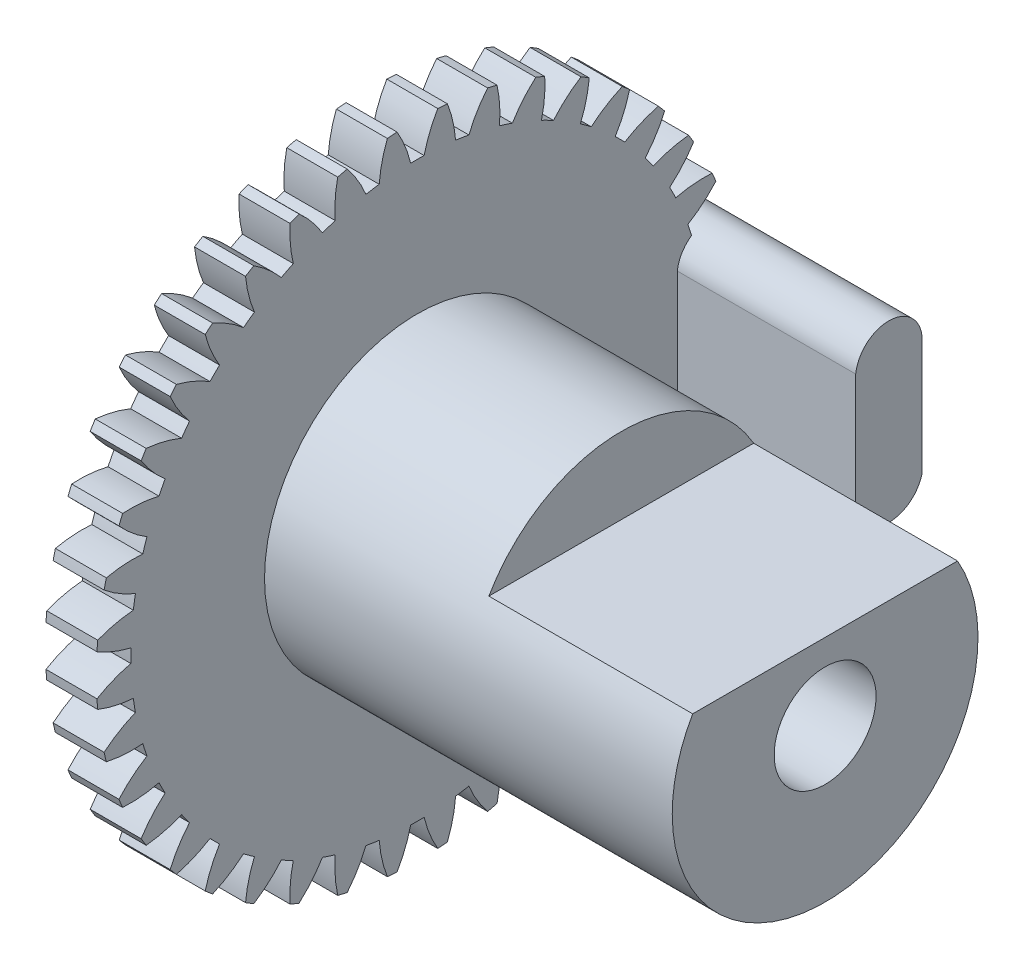
SolidWorks part; units mm, degrees
material "ABS PC"
ref_plane "Plane1" through (0, 0, 0) normal (0, 0, 1) x (1, 0, 0)
ref_plane "Plane2" through (0, 0, 0) normal (0, 1, 0) x (1, 0, 0)
ref_plane "Plane3" through (0, 0, 0) normal (1, 0, 0) x (0, 0, -1)
sketch "HoldingSke" plane through (0, 0, 0) normal (0, 1, 0) x (1, 0, 0)
  line L0 (0, 0) -> (2.5535, -2.1426)
  line L1 (-15, 0) -> (100, 0) construction
  line L2 (0, 0) -> (-2.1039, 2.3779)
  line L3 (0, 0) -> (-11.863, 4.5341)
  line L4 (0, 0) -> (6.6156, 5.5511)
  line L5 (0, 0) -> (-46.8476, -17.4728)
  line L6 (0, 0) -> (-0.829, -0.5593)
  line L7 (-2.1039, 2.3779) -> (8.6586, 51.2059)
  line L8 (-76.2, 54.61) -> (-75.9, 54.61)
  line L9 (-71.009, 38.7566) -> (-53.1078, 45.2721)
  line L10 (-76.2, 71.12) -> (104.1128, 71.12)
  line L11 (0, 0) -> (-1, 0)
  line L12 (-76.2, 101.6) -> (-76.19, 101.6)
  line L13 (24.9733, 27.94) -> (52.9518, 28.4284)
  line L14 (24.9733, 27.94) -> (24.9743, 27.94)
  line L15 (24.9733, 27.94) -> (100.4006, 29.5858)
  line L16 (-63.627, -0.3) -> (-12.827, -0.3)
  circle A0 centre (0, 0) radius 1
  circle A1 centre (0, 0) radius 5.624
  circle A2 centre (0, 0) radius 37.5
  circle A3 centre (0, 0) radius 1
  dimension "MHD" = 11.248
  dimension "Hub_dia" = 75
  dimension "Bore" = 2
  dimension "MBD" = 2
  dimension "Num_teeth" = 40
  dimension "Pitch" = 3.3333
  dimension "Overall_len" = 50
  dimension "Show_teeth" = 40
  dimension "Thickness" = 1
  dimension "OAL" = 50.0001
  dimension "T_dim" = 0.3
  dimension "Ap" = 20
  dimension "H" = 19.05
  dimension "Pitch_radius" = 180.3128
  dimension "Width" = 1
  dimension "Backlash" = 0.01
  dimension "Addendum_fac" = 1
  dimension "Dedendum_fac" = 1.25
  dimension "Clearance_fac" = 0.25
  dimension "Dedendum_add" = 0.001
  dimension "Module" = 0.3
sketch "BasProSke" plane through (0, 0, 0) normal (0, 1, 0) x (1, 0, 0)
  line L0 (-10, 0) -> (60, 0) construction
  line L1 (0, 0) -> (0, 6.3)
  line L2 (0, 0) -> (1, 0)
  line L3 (1, 0) -> (1, 6.3)
  line L4 (1, 6.3) -> (0, 6.3)
  dimension "Thickness" = 1
  dimension "Diameter" = 12.6
revolve "Base-Revolve" add sketch "BasProSke" angle 360 about L0
sketch "TooCutSke" plane through (0, 0, 0) normal (1, 0, 0) x (0, 0, -1)
  line L1 (0, 0) -> (0, 107) construction
  line L2 (0, 0) -> (-0.2531, 5.9947) construction
  line L3 (0, 0) -> (-0.9409, 11.9551) construction
  line L4 (-0.2531, 5.9947) -> (-0.4704, 5.9776) construction
  arc A0 (0.1321, 5.6224) -> (-0.1321, 5.6224) centre (0, 0) ccw
  arc A1 (0.4141, 6.3118) -> (-0.4141, 6.3118) centre (0, 0) ccw
  circle A2 centre (0, 0) radius 6 construction
  circle A3 centre (0, 0) radius 5.6382 construction
  arc A4 (-0.1321, 5.6224) -> (-0.4141, 6.3118) centre (-2.4676, 5.0695) ccw
  arc A5 (0.4141, 6.3118) -> (0.1321, 5.6224) centre (2.4676, 5.0695) ccw
  dimension "Root_dia" = 11.248
  dimension "Overcut_dia" = 12.6508
  dimension "Pitch_dia" = 12
  dimension "Base_dia" = 11.2763
  dimension "Flank_rad" = 2.4
  dimension "Half_ang" = 4.5
  dimension "Half_CT" = 0.2181
extrude "ToothCut" cut sketch "TooCutSke" along normal through all
fillet "Breaks" [suppressed] radius 0.006
fillet "RootFillets" [suppressed] radius 0.076
pattern_circular "TeethCuts" count 40 every 9 about axis through (-10, 0, 0) along (1, 0, 0) of "ToothCut"
sketch "HubNeaOneSke" plane through (0, 0, 0) normal (-1, 0, 0) x (0, 0, 1)
  circle A0 centre (0, 0) radius 5.624
  dimension "Diameter" = 11.248
extrude "HubNearOne" [suppressed] add sketch "HubNeaOneSke" along normal blind 49.0001
sketch "HubNeaBotSke" plane through (0, 0, 0) normal (-1, 0, 0) x (0, 0, 1)
  circle A0 centre (0, 0) radius 5.624
  dimension "Diameter" = 11.248
extrude "HubNearBoth" [suppressed] add sketch "HubNeaBotSke" along normal blind 24.5
ref_plane "FarPln" through (1, 0, 0) normal (1, 0, 0) x (0, 0, -1)
sketch "HubFarSke" plane through (1, 0, 0) normal (1, 0, 0) x (0, 0, -1)
  circle A0 centre (0, 0) radius 5.624
  dimension "Diameter" = 11.248
extrude "HubFar" [suppressed] add sketch "HubFarSke" along normal blind 24.5
sketch "BorSke" plane through (0, 0, 0) normal (1, 0, 0) x (0, 0, -1)
  circle A0 centre (0, 0) radius 1
  dimension "Diameter" = 2
extrude "Bore" cut sketch "BorSke" along normal mid plane 100.0001
sketch "KeySke" plane through (0, 0, 0) normal (1, 0, 0) x (0, 0, -1)
  line L0 (-0.4, 0) -> (-0.4, 1.3)
  line L1 (-0.4, 1.3) -> (0.4, 1.3)
  line L2 (0.4, 1.3) -> (0.4, 0)
  line L3 (0, 0) -> (0, 34) construction
  line L4 (-0.4, 0) -> (0.4, 0)
  dimension "Offset" = 1.3
  dimension "Width" = 0.8
extrude "Keyway" [suppressed] cut sketch "KeySke" along normal mid plane 100.0001
pattern_circular "Keyway2" [suppressed] count 2 every 90 about axis through (-10, 0, 0) along (1, 0, 0)
sketch "Schizzo1" plane through (1, 0, 0) normal (1, 0, 0) x (0, 0, -1)
  circle A0 centre (0, 0) radius 1
  circle A1 centre (0, 0) radius 3
  circle A2 centre (0, 0) radius 1 construction
  dimension "D1" = 6
extrude "Estrusione-Estrusione1" add sketch "Schizzo1" along normal blind 8
sketch "Schizzo2" plane through (9, 0, 0) normal (1, 0, 0) x (0, 0, -1)
  line L0 (-2.5981, 1.5) -> (2.5981, 1.5)
  circle A0 centre (0, 0) radius 3 construction
  arc A1 (2.5981, 1.5) -> (-2.5981, 1.5) centre (0, 0) ccw
  dimension "D1" = 1.5
extrude "Taglio-Estrusione1" cut sketch "Schizzo2" against normal blind 4
sketch "Schizzo3" plane through (1, 0, 0) normal (1, 0, 0) x (0, 0, -1)
  line L0 (5.75, 1.1) -> (5.75, -1) construction
  line L1 (6.4, 1.1752) -> (6.4, -1.1752)
  line L2 (5.1, 1.1752) -> (5.1, -1.1752)
  line L4 (5.75, 0) -> (0, 0) construction
  arc A0 (6.4, 1.1752) -> (5.1, 1.1752) centre (5.75, 1.1) ccw
  arc A1 (5.1, -1.1752) -> (6.4, -1.1752) centre (5.75, -1) ccw
  point P16 (5.1, 0)
  dimension "D1" = 2.1
  dimension "D2" = 1.3
  dimension "D3" = 5.75
  dimension "D4" = 1
  dimension "D5" = 2.3505
extrude "Estrusione-Estrusione2" add sketch "Schizzo3" along normal blind 4.5 from surface at -1 starting at face at (0, 0, -1)
equation "' \"Module@HoldingSke\" = 6.35"
equation "' \"Num_teeth@HoldingSke\" = 12"
equation "' \"Ap@HoldingSke\" =  20"
equation "' \"Ap@HoldingSke\" = 20"
equation "' \"Width@HoldingSke\" = 0.5 * 25.4"
equation "' \"Hub_dia@HoldingSke\"= 1 * 25.4"
equation "' \"Hub_dia@HoldingSke\" = 1 * 25.4"
equation "' \"Overall_len@HoldingSke\" = 1.0 * 25.4"
equation "' \"Bore@HoldingSke\" = 0.75 * 25.4"
equation "' \"T_dim@HoldingSke\" = 0.1 * 25.4"
equation "' \"Width@KeySke\" = 0.25 * 25.4"
equation "' \"Show_teeth@HoldingSke\" = 13"
equation "' \"Backlash@HoldingSke\" = 0.009 * 25.4"
equation "' \"Addendum_fac@HoldingSke\" = 1.0"
equation "' \"Dedendum_fac@HoldingSke\" = 1.25"
equation "' \"Dedendum_add@HoldingSke\" = 0.00005 * 25.4"
equation "' \"Clearance_fac@HoldingSke\" = 0.25"
equation "\"Pitch@HoldingSke\" = 1 / \"Module@HoldingSke\""
equation "\"Overcut_dia@TooCutSke\" = (\"Num_teeth@HoldingSke\" + 2 * \"Addendum_fac@HoldingSke\") / \"Pitch@HoldingSke\" + 0.002 * 25.4"
equation "\"Pitch_dia@TooCutSke\" = \"Num_teeth@HoldingSke\" / \"Pitch@HoldingSke\""
equation "\"Base_dia@TooCutSke\" = \"Num_teeth@HoldingSke\" / \"Pitch@HoldingSke\" * cos((\"Ap@HoldingSke\"  * 3.14159265 / 180))"
equation "\"Root_dia@TooCutSke\" = (\"Num_teeth@HoldingSke\" + 2) / \"Pitch@HoldingSke\" - 2 * (\"Addendum_fac@HoldingSke\" + \"Dedendum_fac@HoldingSke\") / \"Pitch@HoldingSke\" - \"Dedendum_add@HoldingSke\" * 2"
equation "\"Half_ang@TooCutSke\" = 180 / \"Num_teeth@HoldingSke\""
equation "\"Half_CT@TooCutSke\" = \"Num_teeth@HoldingSke\" / \"Pitch@HoldingSke\" * sin((3.14159265 / 2 / \"Num_teeth@HoldingSke\")) / 2 - 7 * \"Backlash@HoldingSke\" / 4"
equation "\"Flank_rad@TooCutSke\" = \"Num_teeth@HoldingSke\" / \"Pitch@HoldingSke\" / 5"
equation "\"Radius@RootFillets\" = \"Clearance_fac@HoldingSke\" / \"Pitch@HoldingSke\" + \"Dedendum_add@HoldingSke\""
equation "\"Break_rad@Breaks\" = 0.02 / \"Pitch@HoldingSke\""
equation "\"Thickness@HoldingSke\" = \"Width@HoldingSke\""
equation "\"OAL@HoldingSke\" = \"Thickness@HoldingSke\""
equation "\"MHD@HoldingSke\" = (\"Num_teeth@HoldingSke\" + 2) / \"Pitch@HoldingSke\" - 2 * (\"Addendum_fac@HoldingSke\" + \"Dedendum_fac@HoldingSke\")  / \"Pitch@HoldingSke\" - \"Dedendum_add@HoldingSke\" * 2"
equation "\"MBD@HoldingSke\" = (\"Num_teeth@HoldingSke\" + 2) / \"Pitch@HoldingSke\" - 2 * (\"Addendum_fac@HoldingSke\" + \"Dedendum_fac@HoldingSke\")  / \"Pitch@HoldingSke\" - \"Dedendum_add@HoldingSke\" * 2 - 0.002 * 25.4"
equation "\"MHD@HoldingSke\" = ((sgn( \"MHD@HoldingSke\" - \"Hub_dia@HoldingSke\" )-1)*( \"MHD@HoldingSke\" - \"Hub_dia@HoldingSke\" ))/-2+ \"Hub_dia@HoldingSke\""
equation "\"MBD@HoldingSke\" = ((sgn( \"MBD@HoldingSke\" - \"Bore@HoldingSke\" )-1)*( \"MBD@HoldingSke\" - \"Bore@HoldingSke\" ))/-2+ \"Bore@HoldingSke\""
equation "\"OAL@HoldingSke\" = ((sgn( \"OAL@HoldingSke\" - \"Overall_len@HoldingSke\" )+1)*( \"OAL@HoldingSke\" - \"Overall_len@HoldingSke\" ))/2 + \"Overall_len@HoldingSke\" + 0.000002 * 25.4"
equation "\"Num_teeth@TeethCuts\" = int( \"Show_teeth@HoldingSke\" ) + 1"
equation "\"Num_teeth@TeethCuts\" = ((sgn( \"Num_teeth@TeethCuts\" - \"Num_teeth@HoldingSke\" )-1)*( \"Num_teeth@TeethCuts\" - \"Num_teeth@HoldingSke\" ))/-2+ \"Num_teeth@HoldingSke\""
equation "\"Num_teeth@TeethCuts\" = ((sgn( \"Num_teeth@TeethCuts\" - 2.0)+1)*( \"Num_teeth@TeethCuts\" - 2.0))/2 +2.0"
equation "\"Angle@TeethCuts\" = 360.0 / \"Num_teeth@HoldingSke\""
equation "\"Diameter@BasProSke\" = (\"Num_teeth@HoldingSke\" + 2 * \"Addendum_fac@HoldingSke\") / \"Pitch@HoldingSke\""
equation "\"Thickness@BasProSke\"  = \"Thickness@HoldingSke\""
equation "' \"Fillet_rad@BasProSke\" =  \"Thickness@HoldingSke\" * 0.05"
equation "' \"Fillet_rad@BasProSke\" = \"Thickness@HoldingSke\" * 0.05"
equation "\"MHD@HoldingSke\" = ((sgn( \"MHD@HoldingSke\" - \"Root_dia@TooCutSke\" )-1)*( \"MHD@HoldingSke\" - \"Root_dia@TooCutSke\" ))/-2+ \"Root_dia@TooCutSke\""
equation "\"Diameter@HubNeaOneSke\" = \"MHD@HoldingSke\""
equation "\"Length@HubNearOne\" = \"OAL@HoldingSke\" - \"Thickness@BasProSke\""
equation "\"Diameter@HubNeaBotSke\" = \"MHD@HoldingSke\""
equation "\"Length@HubNearBoth\" = ( \"OAL@HoldingSke\" - \"Thickness@BasProSke\" ) / 2.0"
equation "\"Thickness@FarPln\" = \"Thickness@BasProSke\""
equation "\"Diameter@HubFarSke\" = \"MHD@HoldingSke\""
equation "\"Length@HubFar\" = ( \"OAL@HoldingSke\" - \"Thickness@BasProSke\" ) / 2.0"
equation "\"Diameter@BorSke\" = \"MBD@HoldingSke\""
equation "\"D1@Bore\" = \"OAL@HoldingSke\" * 2.0"
equation "\"D1@Keyway\" = \"OAL@HoldingSke\" * 2.0"
equation "\"Offset@KeySke\" = \"T_dim@HoldingSke\" + \"MBD@HoldingSke\" / 2.0"
